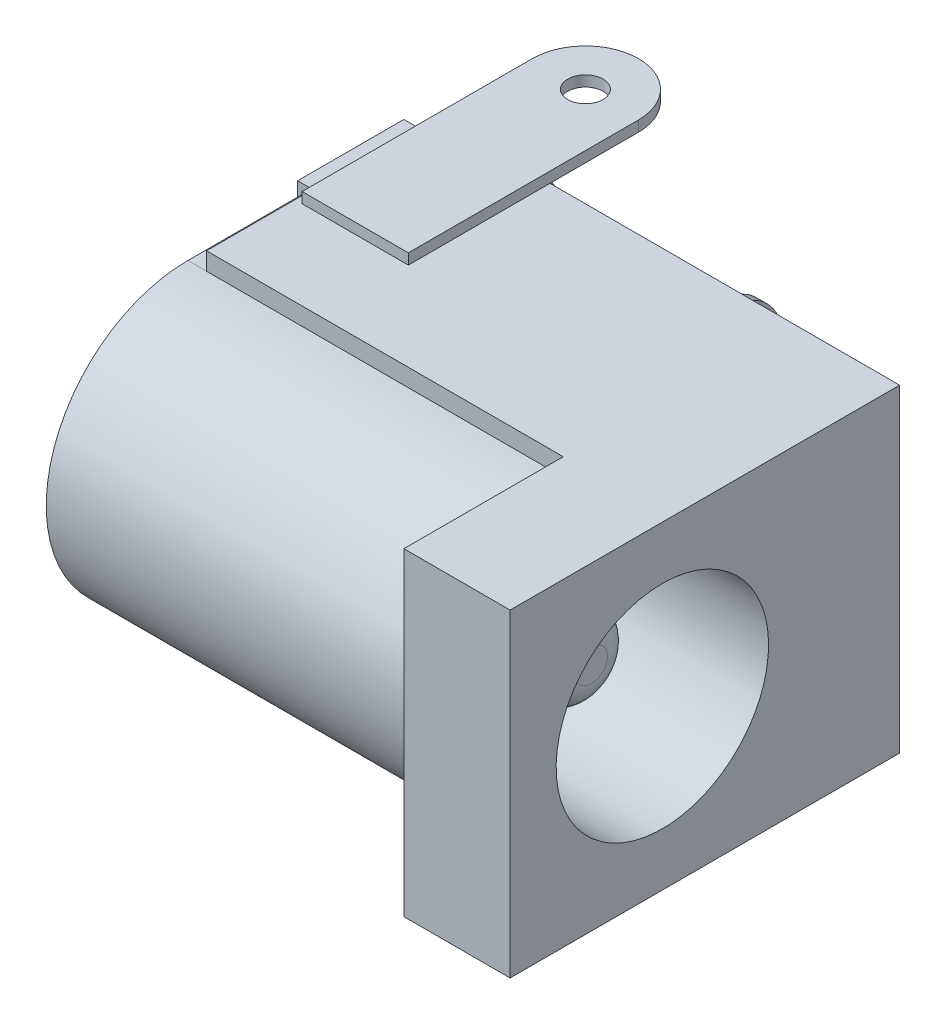
SolidWorks part; units mm, degrees
ref_plane "Front Plane" through (0, 0, 0) normal (0, 0, 1) x (1, 0, 0)
ref_plane "Top Plane" through (0, 0, 0) normal (0, 1, 0) x (1, 0, 0)
ref_plane "Right Plane" through (0, 0, 0) normal (1, 0, 0) x (0, 0, -1)
sketch "Sketch1" plane through (0, 0, 0) normal (0, 0, 1) x (1, 0, 0)
  line L1 (7, 4.5) -> (-5.8734, 4.5)
  line L2 (7, 4.5) -> (7, -4.5)
  line L3 (7, -4.5) -> (-5.8734, -4.5)
  line L4 (-7, 4) -> (-7, -4)
  line L8 (-5.8734, -4) -> (-7, -4)
  line L9 (-5.8734, 4) -> (-7, 4)
  line L10 (-5.8734, 4) -> (-5.8734, 4.5)
  line L11 (-5.8734, -4) -> (-5.8734, -4.5)
extrude "Boss-Extrude1" add sketch "Sketch1" along normal blind 6.5
sketch "Sketch2" plane through (7, 0, 0) normal (1, 0, 0) x (0, 0, -1)
  line L0 (-6.5, -4.5) -> (-6.5, 4.5) construction
  circle A0 centre (-6.5, 0) radius 4
extrude "Boss-Extrude2" add sketch "Sketch2" against normal up to surface (14 mm away) up to face at (-7, 0, 3.25)
sketch "Sketch3" plane through (7, 0, 0) normal (1, 0, 0) x (0, 0, -1)
  line L1 (-6.5, -4.5) -> (-11, -4.5)
  line L2 (-6.5, 4.5) -> (-11, 4.5)
  line L3 (-6.5, 4.5) -> (-6.5, -4.5)
  line L6 (-11, 0.7826) -> (-11, -4.5)
  line L7 (-11, -4.5) -> (-11, 4.5)
  line M1 (-6.5, 4.5) -> (-6.5, 4)
  arc M2 (-6.5, 4) -> (-6.5, -4) centre (-6.5, 0) ccw
  line M3 (-6.5, -4) -> (-6.5, -4.5)
extrude "Boss-Extrude3" add sketch "Sketch3" against normal blind 3 contours L7 L6 L1 L2 M3 M2 M1
sketch "Sketch4" plane through (-7, 0, 0) normal (-1, 0, 0) x (0, 0, 1)
  line L0 (3, 4) -> (3, 2)
  line L1 (6.5, 4) -> (0, 4) construction
  line L2 (6.5, -4) -> (0, -4) construction
  line L3 (0, -4.95) -> (0, 4.95) construction
  line L4 (6.5, 4) -> (3, 4)
  line L5 (6.5, -4) -> (3, -4)
  line L6 (0, 2) -> (3, 2)
  line L7 (0, -2) -> (3, -2)
  line L8 (6.05, 0) -> (-6.05, 0) construction
  line L9 (0, 2) -> (0, -2)
  line L10 (3, -2) -> (3, -4)
  arc A0 (6.5, -4) -> (6.5, 4) centre (6.5, 0) ccw
  dimension "D1" = 3
  dimension "D2" = 2
  dimension "D3" = 2
extrude "Cut-Extrude1" cut sketch "Sketch4" against normal blind 0.4
sketch "Sketch5" plane through (0, 4.5, 0) normal (0, 1, 0) x (1, 0, 0)
  line L0 (-2.8734, 0) -> (-2.8734, -4)
  line L1 (-4.95, 0) -> (4.95, 0) construction
  line L2 (-5.8734, -4) -> (-2.8734, -4)
  line L3 (-5.8734, -6.5) -> (-5.8734, 0) construction
  line L5 (-5.8734, 0) -> (-2.8734, 0)
  line L6 (-2.8734, 0) -> (-5.8734, 0)
  line L8 (-2.8734, -4) -> (-5.8734, -4)
  line L9 (-5.8734, 0) -> (-5.8734, -4)
  line L10 (-5.8734, -4) -> (-5.8734, 0)
  line M3 (7, 0) -> (-5.8734, 0)
  line M4 (-5.8734, 0) -> (-5.8734, -6.5)
  dimension "D2" = 4
extrude "Boss-Extrude4" add sketch "Sketch5" along normal blind 0.3 contours L2 L0 M4 M3
sketch "Sketch6" plane through (0, 0, 0) normal (0, 0, -1) x (-1, 0, 0)
  line L1 (5.8734, 4.8) -> (2.8734, 4.8)
  line L2 (5.8734, 4.8) -> (5.8734, 4.5)
  line L3 (5.8734, 4.5) -> (2.8734, 4.5)
  line L4 (2.8734, 4.8) -> (2.8734, 4.5)
extrude "Boss-Extrude5" add sketch "Sketch6" along normal blind 4
sketch "Sketch7" plane through (0, 4.8, 0) normal (0, 1, 0) x (1, 0, 0)
  line L1 (-5.8734, 4) -> (-5.8734, -4) construction
  line L2 (-2.8734, 4) -> (-2.8734, -4) construction
  line L4 (-5.8734, 2.5) -> (-5.8734, 4)
  line L5 (-5.8734, 4) -> (-2.8734, 4)
  line L6 (-2.8734, 4) -> (-2.8734, 2.5)
  line L7 (-5.8734, 2.5) -> (-5.8734, 4)
  arc A0 (-2.8734, 2.5) -> (-5.8734, 2.5) centre (-4.3734, 2.5) ccw
  circle A1 centre (-4.3734, 2.5) radius 0.5
  point P7 (0, 0)
  line M2 (-5.8734, 4) -> (-5.8734, -4)
  line M4 (-2.8734, -4) -> (-2.8734, 4)
  line M5 (-2.8734, 4) -> (-5.8734, 4)
extrude "Cut-Extrude4" cut sketch "Sketch7" against normal through all contours A1 | A0 L5 M2 | A0 M4 M5
sketch "Sketch8" plane through (-5.8734, 0, 0) normal (-1, 0, 0) x (0, 0, 1)
  line L1 (6.5, 4.5) -> (0, 4.5)
  line L2 (6.5, 4.5) -> (6.5, 4)
  line L3 (6.5, 4) -> (0, 4)
  line L4 (0, 4.5) -> (0, 4)
  line L5 (0, -4) -> (6.5, -4)
  line L6 (0, -4) -> (0, -4.5)
  line L7 (0, -4.5) -> (6.5, -4.5)
  line L8 (6.5, -4) -> (6.5, -4.5)
extrude "Boss-Extrude6" add sketch "Sketch8" along normal blind 0.2
sketch "Sketch9" plane through (-6.6, 0, 0) normal (-1, 0, 0) x (0, 0, 1)
  line L1 (5.1771, 1.5) -> (0, 1.5)
  line L2 (5.1771, -1.5) -> (0, -1.5)
  line L3 (0, -1.5) -> (0, 1.5)
  line L4 (0, 2) -> (0, -2) construction
  arc A1 (5.1771, -1.5) -> (5.1771, 1.5) centre (6.5, 0) ccw
extrude "Boss-Extrude7" add sketch "Sketch9" along normal blind 0.3
sketch "Sketch10" plane through (0, 0, 0) normal (0, 0, -1) x (-1, 0, 0)
  line L1 (6.9, 1.5) -> (6.6, 1.5)
  line L2 (6.9, 1.5) -> (6.9, -1.5)
  line L3 (6.9, -1.5) -> (6.6, -1.5)
  line L4 (6.6, 1.5) -> (6.6, -1.5)
extrude "Boss-Extrude8" add sketch "Sketch10" along normal up to vertex
sketch "Sketch11" plane through (-6.9, 0, 0) normal (-1, 0, 0) x (0, 0, 1)
  line L1 (-4, -1.5) -> (5.1771, -1.5) construction
  line L2 (5.1771, 1.5) -> (-4, 1.5) construction
  line L5 (-4, 1.5) -> (-2.5, 1.5)
  line L6 (-4, 1.5) -> (-4, -1.5)
  line L7 (-4, -1.5) -> (-2.5, -1.5)
  arc A0 (-2.5, 1.5) -> (-2.5, -1.5) centre (-2.5, 0) ccw
  circle A1 centre (-2.5, 0) radius 0.5
  line M3 (5.1771, 1.5) -> (-4, 1.5)
  line M4 (-4, 1.5) -> (-4, -1.5)
  line M5 (-4, -1.5) -> (5.1771, -1.5)
sketch "Sketch12" plane through (0, 0, 0) normal (0, 0, -1) x (-1, 0, 0)
  line L0 (0.6, 1.5) -> (0.6, -1.5)
  line L1 (6.6, 1.5) -> (6.6, -1.5) construction
  line L2 (0.6, 1.5) -> (0.3, 1.5)
  line L3 (0.3, 1.5) -> (0.3, -1.5)
  line L4 (0.3, -1.5) -> (0.6, -1.5)
  line L5 (7.7, 0) -> (-7.7, 0) construction
  dimension "D1" = 6
  dimension "D2" = 1.5
  dimension "D3" = 0.3
extrude "Boss-Extrude9" add sketch "Sketch12" along normal up to surface (4 mm away) up to face at (-6.75, 0, -4)
extrude "Cut-Extrude5" cut sketch "Sketch11" against normal through all contours A1 | A0 M3 M4 | A0 L6 M5
sketch "Sketch13" plane through (7, 0, 0) normal (1, 0, 0) x (0, 0, -1)
  line L0 (-11, 0) -> (-6.7, 0)
  line L1 (-11, -4.5) -> (-11, 4.5) construction
  line L2 (7.7, 0) -> (-7.7, 0) construction
  circle A0 centre (-6.7, 0) radius 3
extrude "Cut-Extrude6" cut sketch "Sketch13" against normal blind 10
sketch "Sketch14" plane through (-6.9, 0, 0) normal (-1, 0, 0) x (0, 0, 1)
  circle A0 centre (6.5, 0) radius 1.5
  circle A1 centre (6.5, 0) radius 0.5
extrude "Boss-Extrude10" add sketch "Sketch14" along normal blind 0.5 contours A0
sketch "Sketch15" plane through (-7.4, 0, 0) normal (-1, 0, 0) x (0, 0, 1)
  circle A0 centre (6.5, 0) radius 0.5
extrude "Cut-Extrude7" cut sketch "Sketch15" against normal blind 1
fillet "Fillet1" radius 0.5 1 edges at (-7.4, 0, 7)
fillet "Fillet2" radius 0.25 1 edges at (-7.4, 0, 8)
sketch "Sketch16" plane through (-3, 0, 0) normal (1, 0, 0) x (0, 0, -1)
  circle A0 centre (-6.7, 0) radius 1.2
extrude "Boss-Extrude11" add sketch "Sketch16" along normal blind 8
fillet "Fillet4" radius 0.75 1 edges at (5, 1.2, 6.7)
